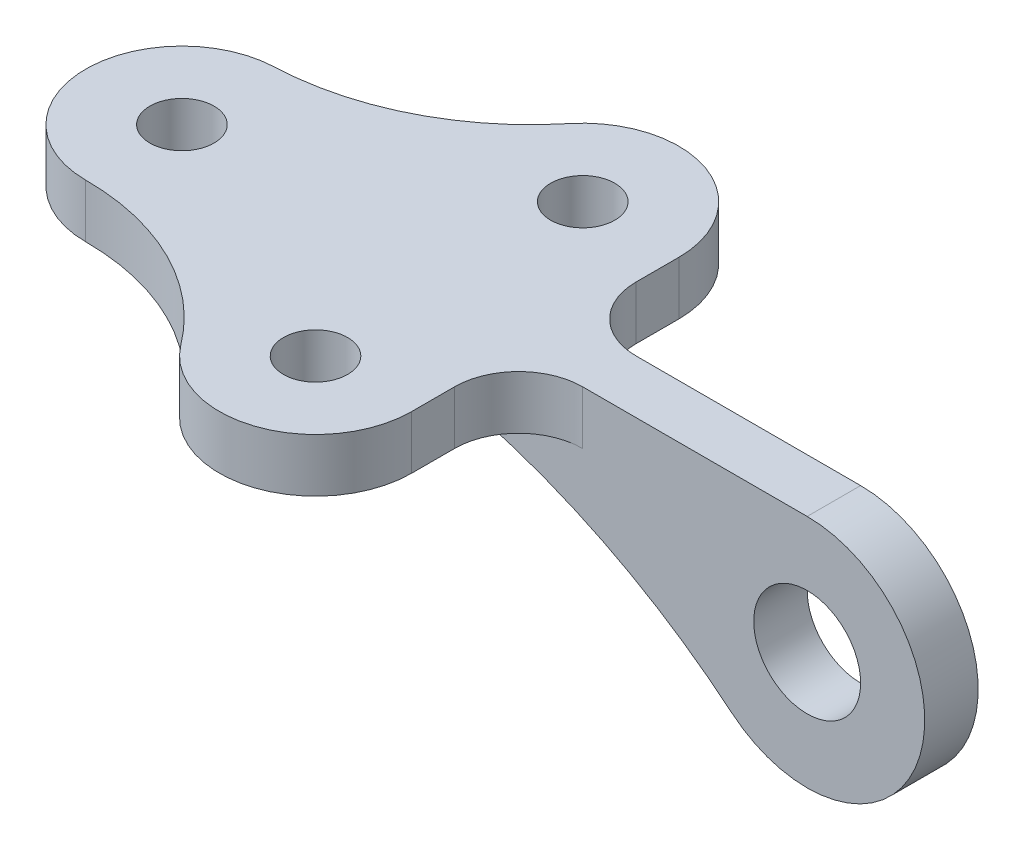
SolidWorks part; units mm, degrees
ref_plane "Front Plane" through (0, 0, 0) normal (0, 0, 1) x (1, 0, 0)
ref_plane "Top Plane" through (0, 0, 0) normal (0, 1, 0) x (1, 0, 0)
ref_plane "Right Plane" through (0, 0, 0) normal (1, 0, 0) x (0, 0, -1)
sketch "Sketch2" plane through (0, 0, 0) normal (0, 1, 0) x (1, 0, 0)
  line L0 (68, -25) -> (68, 25)
  arc A0 (-0.7207, 17.9856) -> (0, -18) centre (0, 0) ccw
  circle A1 centre (0, 0) radius 6
  arc A2 (35.6, -35.8) -> (68, -25) centre (50, -25) ccw
  circle A3 centre (50, -25) radius 6
  arc A4 (68, 25) -> (36.044, 36.3679) centre (50, 25) ccw
  circle A5 centre (50, 25) radius 6
  arc A6 (-0.7207, 17.9856) -> (36.044, 36.3679) centre (-2.7227, 67.9455) ccw
  arc A7 (35.6, -35.8) -> (0, -18) centre (0, -62.5) ccw
  point P1 (0, 0)
  point P6 (0, 0)
  dimension "D1" = 36
  dimension "D2" = 12
  dimension "D3" = 36
  dimension "D4" = 12
  dimension "D5" = 36
  dimension "D6" = 12
  dimension "D10" = 100
  dimension "D7" = 25
  dimension "D8" = 25
  dimension "D9" = 50
extrude "Boss-Extrude1" add sketch "Sketch2" along normal mid plane 10
sketch "Sketch3" plane through (0, 0, 0) normal (0, 0, 1) x (1, 0, 0)
  line L0 (35.6, 5) -> (0, 5) construction
  line L1 (12, 5) -> (122, 5)
  line L2 (12, 5) -> (12, -5)
  line L5 (0, -5) -> (35.6, -5) construction
  line L7 (12, -5) -> (27.9787, -5)
  arc A0 (107.9288, -33.9116) -> (122, 5) centre (122, -17) ccw
  circle A1 centre (122, -17) radius 10
  arc A2 (107.9288, -33.9116) -> (27.9787, -5) centre (27.9787, -130) ccw
  dimension "D3" = 44
  dimension "D4" = 20
  dimension "D1" = 250
  dimension "D5" = 10
  dimension "D2" = 110
  dimension "D6" = 12
  dimension "D7" = 15.9787
extrude "Boss-Extrude2" add sketch "Sketch3" against normal mid plane 10
fillet "Fillet1" radius 12 2 edges at (68, 0, 5) (68, 0, -5)
